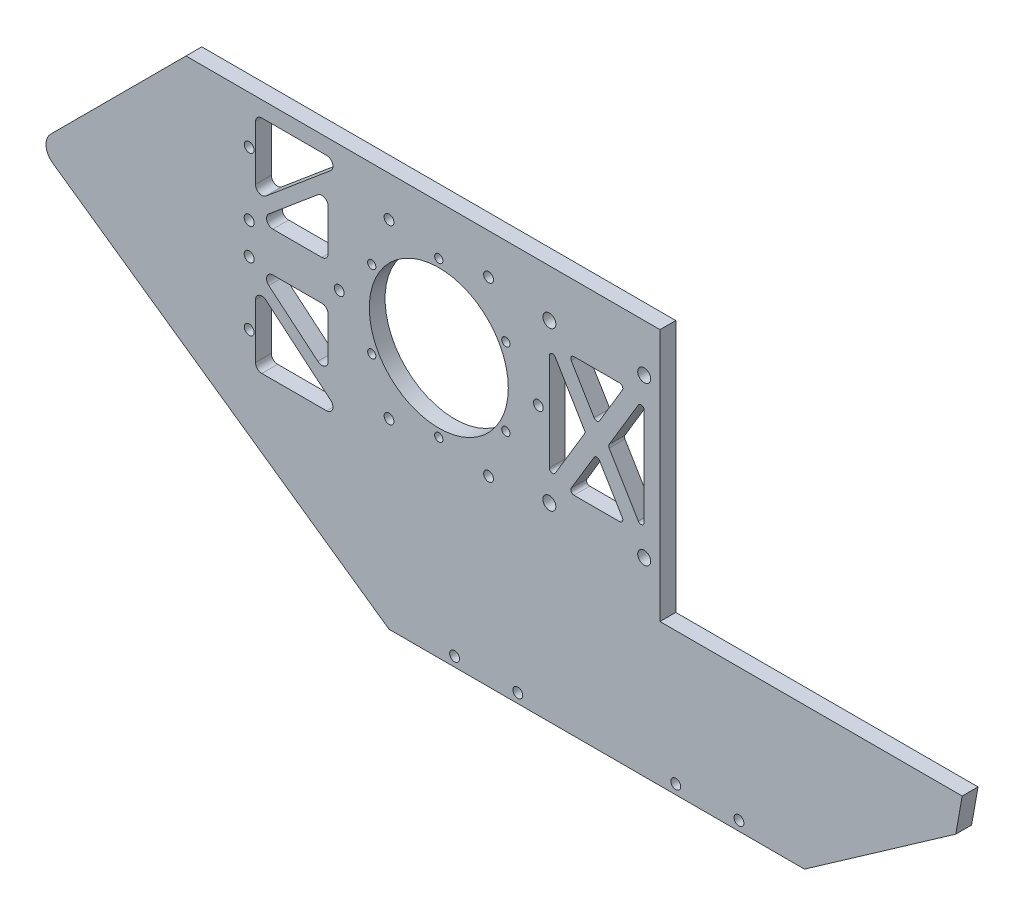
SolidWorks part; units mm, degrees
ref_plane "前视基准面" through (0, 0, 0) normal (0, 0, 1) x (1, 0, 0)
ref_plane "上视基准面" through (0, 0, 0) normal (0, 1, 0) x (1, 0, 0)
ref_plane "右视基准面" through (0, 0, 0) normal (1, 0, 0) x (0, 0, -1)
sketch "草图1" plane through (0, 0, 0) normal (0, 0, 1) x (1, 0, 0)
  line L1 (-80, 40) -> (70, 40)
  line L2 (-80, 40) -> (-80, -40)
  line L3 (-80, -40) -> (70, -40)
  line L4 (70, 40) -> (70, -40)
  circle A0 centre (0, 0) radius 24.5 construction
  circle A1 centre (0, -24.5) radius 1.3
  circle A2 centre (-21.2176, -12.25) radius 1.3
  circle A3 centre (-21.2176, 12.25) radius 1.3
  circle A4 centre (0, 0) radius 22
  circle A5 centre (0, 24.5) radius 1.3
  circle A6 centre (21.2176, 12.25) radius 1.3
  circle A7 centre (21.2176, -12.25) radius 1.3
  point P11 (0, 0)
  point P15 (70, 0)
  dimension "D1" = 49
  dimension "D2" = 2.6
  dimension "D4" = 44
  dimension "D5" = 80
  dimension "D6" = 70
  dimension "D7" = 80
  dimension "D3" = 6
extrude "凸台-拉伸1" add sketch "草图1" along normal blind 5
sketch "草图3" plane through (0, 0, 5) normal (0, 0, 1) x (1, 0, 0)
  line L0 (0, 0) -> (-60, 0) construction
  line L1 (-60, 0) -> (-60, -25) construction
  line L3 (-60, 0) -> (-60, 24.3133)
  circle A4 centre (-60, -25) radius 1.55
  circle A5 centre (-60, -5) radius 1.5828
  circle A6 centre (-60, 25) radius 1.55
  circle A7 centre (-60, 5) radius 1.5828
  point P6 (-60, 0)
  dimension "D3" = 3.1
  dimension "D4" = 20
  dimension "D1" = 60
  dimension "D2" = 25
extrude "切除-拉伸3" cut sketch "草图3" against normal blind 12.5
sketch "草图4" plane through (0, 0, 5) normal (0, 0, 1) x (1, 0, 0)
  line L0 (-58, 35) -> (-30, 35)
  line L1 (-30, 35) -> (-58, 11.5052)
  line L2 (-58, 11.5052) -> (-58, 35)
  line L3 (-35, 25.5829) -> (-58, 6.2836)
  line L4 (-58, 6.2836) -> (-35, 6.2836)
  line L5 (-35, 6.2836) -> (-35, 25.5829)
  line L8 (70, 40) -> (-80, 40) construction
  line L9 (-80, 40) -> (-80, -40) construction
  dimension "D1" = 5
  dimension "D2" = 22
  dimension "D3" = 140
  dimension "D4" = 45
  dimension "D6" = 4
extrude "切除-拉伸5" cut sketch "草图4" against normal blind 8 contours L2 L0 L1 | L5 L3 L4
fillet "圆角3" radius 2 6 edges at (-35, 6.2836, 2.5) (-58, 6.2836, 2.5) (-35, 25.5829, 2.5) (-30, 35, 2.5) (-58, 11.5052, 2.5) (-58, 35, 2.5)
mirror "镜向2" about plane through (0, 0, 0) normal (0, 1, 0) of "圆角3", "切除-拉伸5"
sketch "草图10" plane through (0, 0, 5) normal (0, 0, 1) x (1, 0, 0)
  line L0 (-80, -40) -> (-127.0531, -7.0531)
  line L1 (-127.0531, -7.0531) -> (-80, 40)
  line L2 (-80, -40) -> (70, -40) construction
  line L3 (-80, 40) -> (-80, -40) construction
  line L4 (-80, 40) -> (-80, -40)
  dimension "D1" = 145
  dimension "D2" = 45
extrude "凸台-拉伸4" add sketch "草图10" against normal up to surface (5 mm away) contours L4 L0 L1 up to face at (-49.3474, 27.3903, 0)
fillet "圆角5" radius 5 1 edges at (-127.0531, -7.0531, 2.5)
sketch "草图11" plane through (0, 0, 5) normal (0, 0, 1) x (1, 0, 0)
  line L0 (0, 0) -> (0, 34) construction
  line L1 (0, 0) -> (-15.75, 27.2798)
  circle A0 centre (0, 0) radius 29 construction
  circle A1 centre (0, 0) radius 34 construction
  circle A2 centre (0, 0) radius 31.5 construction
  circle A3 centre (-15.75, 27.2798) radius 1.55
  circle A4 centre (15.75, 27.2798) radius 1.55
  circle A5 centre (31.5, 0) radius 1.55
  circle A6 centre (15.75, -27.2798) radius 1.55
  circle A7 centre (-15.75, -27.2798) radius 1.55
  circle A8 centre (-31.5, 0) radius 1.55
  point P20 (0, 0)
  dimension "D1" = 58
  dimension "D2" = 68
  dimension "D3" = 63
  dimension "D5" = 3.1
  dimension "D4" = 30
  dimension "D6" = 6
extrude "切除-拉伸7" cut sketch "草图11" against normal blind 25 contours A3 | A4 | A5 | A6 | A7 | A8
sketch "草图12" plane through (0, 0, 5) normal (0, 0, 1) x (1, 0, 0)
  line L0 (0, 0) -> (50, 0) construction
  line L6 (35, -25) -> (65, -25) construction
  line L7 (35, -25) -> (35, 25) construction
  line L8 (35, 25) -> (65, 25) construction
  line L9 (65, -25) -> (65, 25) construction
  line L10 (35, -25) -> (65, 25) construction
  line L11 (35, 25) -> (65, -25) construction
  circle A0 centre (0, 0) radius 28 construction
  circle A1 centre (35, 25) radius 2.05
  circle A2 centre (65, 25) radius 2.05
  circle A3 centre (65, -25) radius 2.05
  circle A4 centre (35, -25) radius 2.05
  dimension "D3" = 56
  dimension "D5" = 4.1
  dimension "D6" = 4.1
  dimension "D1" = 30
  dimension "D2" = 50
  dimension "D4" = 50
extrude "切除-拉伸8" cut sketch "草图12" against normal blind 10
sketch "草图13" plane through (0, 0, 5) normal (0, 0, 1) x (1, 0, 0)
  line L0 (35, 25) -> (65, -25) construction
  line L6 (35, 25) -> (65, -25) construction
  line L10 (35, 19) -> (35, -19)
  line L11 (35, -19) -> (46.4, 0)
  line L12 (46.4, 0) -> (35, 19)
  line L13 (35, -25) -> (65, 25) construction
  line L14 (50, 0) -> (50, -49.4768) construction
  line L15 (65, -19) -> (53.6, 0)
  line L16 (65, 19) -> (65, -19)
  line L17 (53.6, 0) -> (65, 19)
  line L18 (41, 19) -> (50, 4)
  line L19 (50, 4) -> (59, 19)
  line L20 (59, 19) -> (41, 19)
  line L21 (35, 19) -> (65, 19) construction
  line L22 (50, 0) -> (90.4004, 0) construction
  line L23 (50, -4) -> (59, -19)
  line L24 (41, -19) -> (50, -4)
  line L25 (59, -19) -> (41, -19)
  circle A0 centre (35, -25) radius 2.05 construction
  circle A1 centre (65, 25) radius 2.05 construction
  point P4 (50, 0)
  dimension "D1" = 6
  dimension "D2" = 6
  dimension "D3" = 6
  dimension "D4" = 6
  dimension "D5" = 0
extrude "切除-拉伸9" cut sketch "草图13" against normal blind 10
fillet "圆角6" radius 1 12 edges at (35, -19, 2.5) (46.4, 0, 2.5) (35, 19, 2.5) (41, -19, 2.5) (50, -4, 2.5) (59, -19, 2.5) (65, -19, 2.5) (65, 19, 2.5) (53.6, 0, 2.5) (50, 4, 2.5) (59, 19, 2.5) (41, 19, 2.5)
sketch "草图14" plane through (0, 0, 0) normal (0, 0, -1) x (-1, 0, 0)
  circle A0 centre (0, 24.5) radius 2.25
  circle A1 centre (21.2176, 12.25) radius 2.25
  circle A2 centre (21.2176, -12.25) radius 2.25
  circle A3 centre (0, -24.5) radius 2.25
  circle A4 centre (-21.2176, -12.25) radius 2.25
  circle A5 centre (-21.2176, 12.25) radius 2.25
  point P15 (0, 0)
  dimension "D1" = 4.5
  dimension "D2" = 6
extrude "切除-拉伸10" cut sketch "草图14" against normal blind 2.5
sketch "草图15" plane through (0, 0, 0) normal (0, 0, -1) x (-1, 0, 0)
  line L0 (-50, 19) -> (-50, -132.8609) construction
  line L2 (-57.2338, 19) -> (-42.7662, 19) construction
  line L3 (80, -40) -> (15.7333, -85)
  line L4 (15.7333, -85) -> (-115.7333, -85)
  line L5 (80, -40) -> (-70, -40) construction
  line L6 (122.1719, -10.4709) -> (80, -40) construction
  line L7 (80, -40) -> (-180, -40)
  line L8 (-50, -85) -> (-50, -40)
  line L9 (-180, -40) -> (-115.7333, -85)
  dimension "D1" = 180
  dimension "D2" = 45
extrude "凸台-拉伸5" add sketch "草图15" against normal up to surface (5 mm away) contours L8 L4 L3 L7 | L7 L9 L4 L8 up to face at (50, 13.974, 5)
chamfer "倒角1" distance 20 angle 45 1 edges at (180, -40, 2.5)
sketch "草图16" plane through (0, 0, 0) normal (0, 0, -1) x (-1, 0, 0)
  line L0 (-50, -85) -> (-50, -82)
  line L1 (15.7333, -85) -> (-115.7333, -85) construction
  line L2 (-50, -82) -> (-75, -82) construction
  line L3 (-50, -82) -> (-50, -114.8278) construction
  circle A0 centre (-75, -82) radius 1.55
  circle A1 centre (-95, -82) radius 1.55
  circle A2 centre (-25, -82) radius 1.55
  circle A3 centre (-5, -82) radius 1.55
  dimension "D3" = 3.1
  dimension "D1" = 3
  dimension "D2" = 25
  dimension "D4" = 2
extrude "切除-拉伸11" cut sketch "草图16" against normal blind 10.5 contours A1 | A0 | A2 | A3
